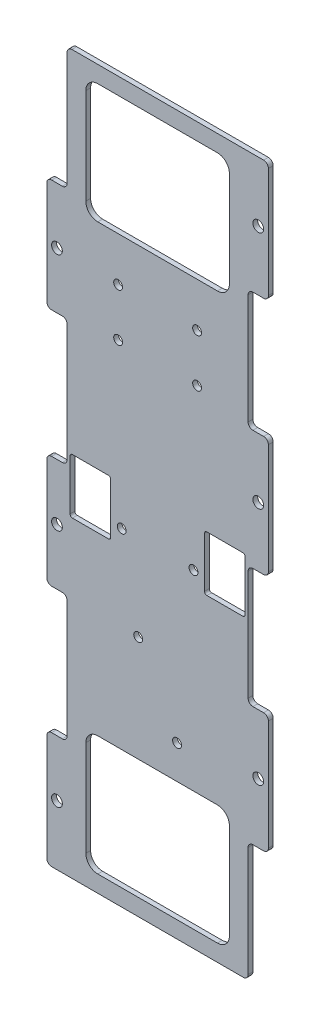
SolidWorks part; units mm, degrees
material "Acrylic (Medium-high impact)"
ref_plane "Front Plane" through (0, 0, 0) normal (0, 0, 1) x (1, 0, 0)
ref_plane "Top Plane" through (0, 0, 0) normal (0, 1, 0) x (1, 0, 0)
ref_plane "Right Plane" through (0, 0, 0) normal (1, 0, 0) x (0, 0, -1)
sketch "Sketch1" plane through (0, 0, 0) normal (0, 0, 1) x (1, 0, 0)
  line L1 (46.3, -150) -> (-46.3, -150)
  line L2 (46.3, -150) -> (46.3, 150)
  line L3 (46.3, 150) -> (-46.3, 150)
  line L4 (-46.3, -150) -> (-46.3, 150)
  line L5 (46.3, -150) -> (-46.3, 150) construction
  line L6 (46.3, 150) -> (-46.3, -150) construction
  point P0 (0, 0)
  dimension "D1" = 300
  dimension "D2" = 92.6
extrude "Boss-Extrude1" add sketch "Sketch1" along normal blind 2
sketch "Sketch3" plane through (0, 0, 0) normal (0, 0, 1) x (1, 0, 0)
  line L0 (-42.06, 151.5) -> (-42.06, -150) construction
  line L1 (42.06, 150) -> (42.06, -148.5) construction
  line L2 (-37.82, 98.5) -> (-46.3, 98.5)
  line L3 (-37.82, 98.5) -> (-37.82, 150)
  line L4 (-37.82, 150) -> (-46.3, 150)
  line L5 (-46.3, 98.5) -> (-46.3, 150)
  line L6 (-37.82, 98.5) -> (-46.3, 150) construction
  line L7 (-37.82, 150) -> (-46.3, 98.5) construction
  line L8 (37.82, 100) -> (46.3, 100)
  line L9 (37.82, 100) -> (37.82, 50)
  line L10 (37.82, 50) -> (46.3, 50)
  line L11 (46.3, 100) -> (46.3, 50)
  line L12 (37.82, 100) -> (46.3, 50) construction
  line L13 (37.82, 50) -> (46.3, 100) construction
  line L14 (46.3, -50) -> (37.82, -50)
  line L15 (46.3, -50) -> (46.3, 0)
  line L16 (46.3, 0) -> (37.82, 0)
  line L17 (37.82, -50) -> (37.82, 0)
  line L18 (46.3, -50) -> (37.82, 0) construction
  line L19 (46.3, 0) -> (37.82, -50) construction
  line L20 (-37.82, -1.5) -> (-46.3, -1.5)
  line L21 (-37.82, -1.5) -> (-37.82, 51.5)
  line L22 (-37.82, 51.5) -> (-46.3, 51.5)
  line L23 (-46.3, -1.5) -> (-46.3, 51.5)
  line L24 (-37.82, -1.5) -> (-46.3, 51.5) construction
  line L25 (-37.82, 51.5) -> (-46.3, -1.5) construction
  line L26 (-37.82, -101.5) -> (-46.3, -101.5)
  line L27 (-37.82, -101.5) -> (-37.82, -48.5)
  line L28 (-37.82, -48.5) -> (-46.3, -48.5)
  line L29 (-46.3, -101.5) -> (-46.3, -48.5)
  line L30 (-37.82, -101.5) -> (-46.3, -48.5) construction
  line L31 (-37.82, -48.5) -> (-46.3, -101.5) construction
  line L32 (37.82, -150) -> (46.3, -150)
  line L33 (37.82, -150) -> (37.82, -100)
  line L34 (37.82, -100) -> (46.3, -100)
  line L35 (46.3, -150) -> (46.3, -100)
  line L36 (37.82, -150) -> (46.3, -100) construction
  line L37 (37.82, -100) -> (46.3, -150) construction
  line L38 (42.06, 50) -> (-134.3061, 50) construction
  line L39 (46.3, 150) -> (-46.3, 150) construction
  line L40 (-46.3, -150) -> (46.3, -150) construction
  circle A0 centre (-42.06, 75) radius 2.25
  circle A1 centre (42.06, 125) radius 2.25
  circle A2 centre (42.06, 25) radius 2.25
  circle A3 centre (42.06, -75) radius 2.25
  circle A4 centre (-42.06, -25) radius 2.25
  circle A5 centre (-42.06, -125) radius 2.25
  point P8 (-42.06, 124.25)
  point P10 (-42.06, 25)
  point P19 (42.06, 75)
  point P24 (-42.06, -75)
  point P32 (42.06, -25)
  point P39 (42.06, -125)
  dimension "D1" = 4.5
  dimension "D2" = 4.5
  dimension "D12" = 4.5
  dimension "D14" = 4.5
  dimension "D20" = 4.5
  dimension "D22" = 4.5
  dimension "D3" = 25
  dimension "D4" = 84.12
  dimension "D5" = 8.48
  dimension "D6" = 51.5
  dimension "D7" = 8.48
  dimension "D8" = 50
  dimension "D9" = 50
  dimension "D10" = 8.48
  dimension "D11" = 75
  dimension "D13" = 125
  dimension "D15" = 100
  dimension "D16" = 53
  dimension "D17" = 53
  dimension "D18" = 8.48
  dimension "D19" = 75
  dimension "D21" = 50
  dimension "D23" = 8.48
  dimension "D24" = 100
  dimension "D25" = 42.06
  dimension "D26" = 0
  dimension "D27" = 0
  dimension "D28" = 0
  dimension "D29" = 0
  dimension "D30" = 175
  dimension "D31" = 25
  dimension "D32" = 125
  dimension "D33" = 75
extrude "Cut-Extrude2" cut sketch "Sketch3" along normal blind 10
fillet "Fillet1" radius 2 24 edges at (-37.82, -1.5, 1) (-46.3, -1.5, 1) (-46.3, -48.5, 1) (-37.82, -48.5, 1) (-37.82, -101.5, 1) (-46.3, -101.5, 1) (-46.3, -150, 1) (37.82, -150, 1) (37.82, -100, 1) (46.3, -100, 1) (46.3, -50, 1) (37.82, -50, 1) (37.82, 0, 1) (46.3, 0, 1) (46.3, 50, 1) (37.82, 50, 1) (37.82, 100, 1) (46.3, 100, 1) (46.3, 150, 1) (-37.82, 150, 1) (-37.82, 98.5, 1) (-46.3, 98.5, 1) (-37.82, 51.5, 1) (-46.3, 51.5, 1)
sketch "Sketch4" plane through (0, 0, 0) normal (0, 0, -1) x (-1, 0, 0)
  circle A0 centre (-8.125, -79) radius 1.85
  circle A1 centre (8.125, -48.8) radius 1.85
  dimension "D1" = 3.7
  dimension "D2" = 3.7
extrude "Cut-Extrude3" cut sketch "Sketch4" against normal blind 5
sketch "Sketch5" plane through (0, 0, 0) normal (0, 0, -1) x (-1, 0, 0)
  line L0 (44.82, -19.5) -> (33.32, -19.5) construction
  line L5 (20.6, 3.5) -> (35.6, 3.5)
  line L6 (19.6, 2.5) -> (19.6, -18.5)
  line L7 (20.6, -19.5) -> (35.6, -19.5)
  line L8 (36.6, 2.5) -> (36.6, -18.5)
  line L9 (21.4, -15.85) -> (34.8, -15.85) construction
  line L10 (19.6, -8) -> (-73.9654, -8) construction
  line L11 (-35.6, 3.5882) -> (-20.6, 3.5882)
  line L12 (-36.6, 2.5882) -> (-36.6, -18.4118)
  line L13 (-35.6, -19.4118) -> (-20.6, -19.4118)
  line L14 (-19.6, 2.5882) -> (-19.6, -18.4118)
  line L15 (-28.1, 2.65) -> (-28.1, -26.7556) construction
  line L16 (-21.4, 2.65) -> (-34.8, 2.65) construction
  circle A0 centre (-15, -13) radius 1.85
  circle A1 centre (15, -13) radius 1.85
  arc A2 (35.6, 3.5) -> (36.6, 2.5) centre (35.6, 2.5) cw
  arc A3 (20.6, 3.5) -> (19.6, 2.5) centre (20.6, 2.5) ccw
  arc A4 (35.6, -19.5) -> (36.6, -18.5) centre (35.6, -18.5) ccw
  arc A5 (19.6, -18.5) -> (20.6, -19.5) centre (20.6, -18.5) ccw
  arc A11 (-20.6, 3.5882) -> (-19.6, 2.5882) centre (-20.6, 2.5882) cw
  arc A12 (-35.6, 3.5882) -> (-36.6, 2.5882) centre (-35.6, 2.5882) ccw
  arc A13 (-20.6, -19.4118) -> (-19.6, -18.4118) centre (-20.6, -18.4118) ccw
  arc A14 (-36.6, -18.4118) -> (-35.6, -19.4118) centre (-35.6, -18.4118) ccw
  point P19 (28.1, -15.85)
  point P22 (36.6, 3.5)
  point P25 (19.6, 3.5)
  point P28 (36.6, -19.5)
  point P31 (19.6, -19.5)
  point P47 (-28.1, 3.5882)
  dimension "D1" = 3.7
  dimension "D2" = 3.7
  dimension "D8" = 1
  dimension "D4" = 17
  dimension "D5" = 8.5
  dimension "D7" = 23
extrude "Cut-Extrude4" cut sketch "Sketch5" against normal blind 10
sketch "Sketch6" plane through (0, 0, 0) normal (0, 0, -1) x (-1, 0, 0)
  circle A0 centre (-16.5, 74.5) radius 1.85
  circle A1 centre (16.5, 74.5) radius 1.85
  circle A2 centre (16.5, 54.5) radius 1.85
  circle A3 centre (-16.5, 54.5) radius 1.85
  dimension "D1" = 3.7
extrude "Cut-Extrude5" cut sketch "Sketch6" against normal blind 8.5
sketch "Sketch7" plane through (0, 0, 0) normal (0, 0, -1) x (-1, 0, 0)
  line L0 (0, 148) -> (0, -150) construction
  line L6 (-42, 148) -> (42, 148) construction
  line L7 (25, 93) -> (-25, 93)
  line L8 (30, 98) -> (30, 138)
  line L9 (25, 143) -> (-25, 143)
  line L10 (-30, 98) -> (-30, 138)
  line L11 (30, 93) -> (-30, 143) construction
  line L12 (30, 143) -> (-30, 93) construction
  line L13 (-42, -148) -> (42, -148) construction
  line L14 (25, -143) -> (-25, -143)
  line L15 (30, -138) -> (30, -98)
  line L16 (25, -93) -> (-25, -93)
  line L17 (-30, -138) -> (-30, -98)
  line L18 (30, -143) -> (-30, -93) construction
  line L19 (30, -93) -> (-30, -143) construction
  arc A0 (30, 138) -> (25, 143) centre (25, 138) ccw
  arc A1 (-25, 143) -> (-30, 138) centre (-25, 138) ccw
  arc A2 (-25, 93) -> (-30, 98) centre (-25, 98) cw
  arc A3 (25, 93) -> (30, 98) centre (25, 98) ccw
  arc A4 (-25, -93) -> (-30, -98) centre (-25, -98) ccw
  arc A5 (-25, -143) -> (-30, -138) centre (-25, -138) cw
  arc A6 (25, -143) -> (30, -138) centre (25, -138) ccw
  arc A7 (30, -98) -> (25, -93) centre (25, -98) ccw
  point P4 (0, 118)
  point P12 (0, -118)
  dimension "D7" = 5
  dimension "D1" = 60
  dimension "D2" = 50
  dimension "D3" = 5
  dimension "D4" = 50
  dimension "D5" = 60
  dimension "D6" = 5
extrude "Cut-Extrude6" cut sketch "Sketch7" against normal blind 8.5
